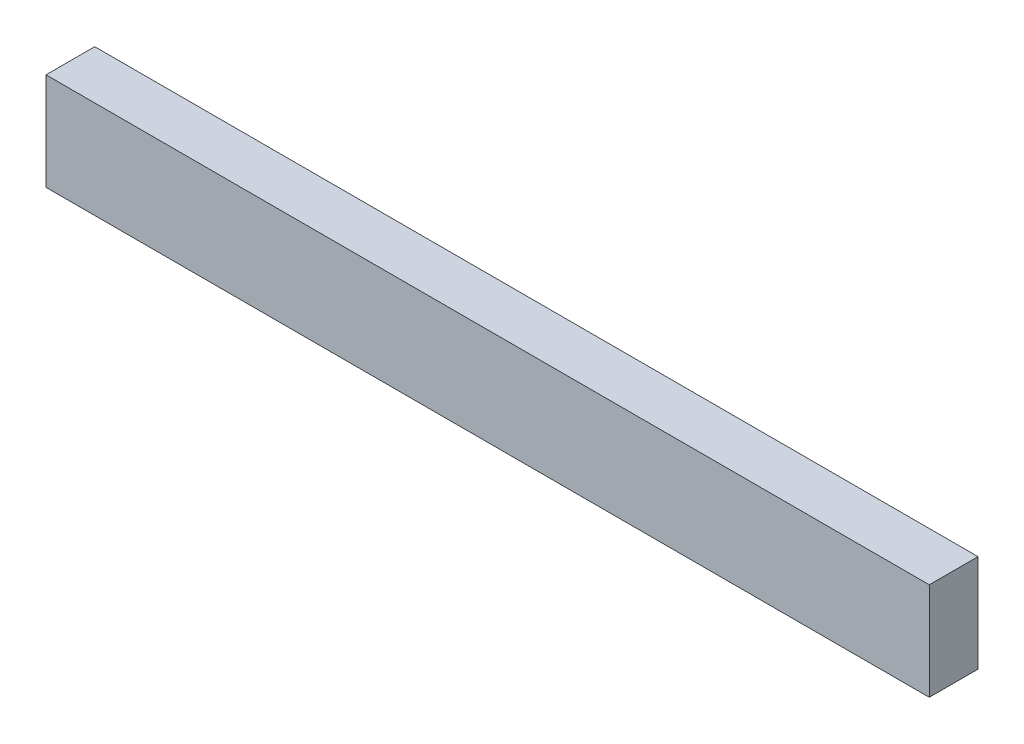
SolidWorks part; units mm, degrees
material "Sapin"
ref_plane "Plan de face" through (0, 0, 0) normal (0, 0, 1) x (1, 0, 0)
ref_plane "Plan de dessus" through (0, 0, 0) normal (0, 1, 0) x (1, 0, 0)
ref_plane "Plan de droite" through (0, 0, 0) normal (1, 0, 0) x (0, 0, -1)
sketch "Esquisse1" plane through (0, 0, 0) normal (0, 0, 1) x (1, 0, 0)
  line L1 (-217.5, -24) -> (217.5, -24)
  line L2 (-217.5, -24) -> (-217.5, 24)
  line L3 (-217.5, 24) -> (217.5, 24)
  line L4 (217.5, -24) -> (217.5, 24)
  line L5 (-217.5, -24) -> (217.5, 24) construction
  line L6 (-217.5, 24) -> (217.5, -24) construction
  point P0 (0, 0)
  dimension "D1" = 48
  dimension "D2" = 435
extrude "Boss.-Extru.1" add sketch "Esquisse1" along normal mid plane 24
